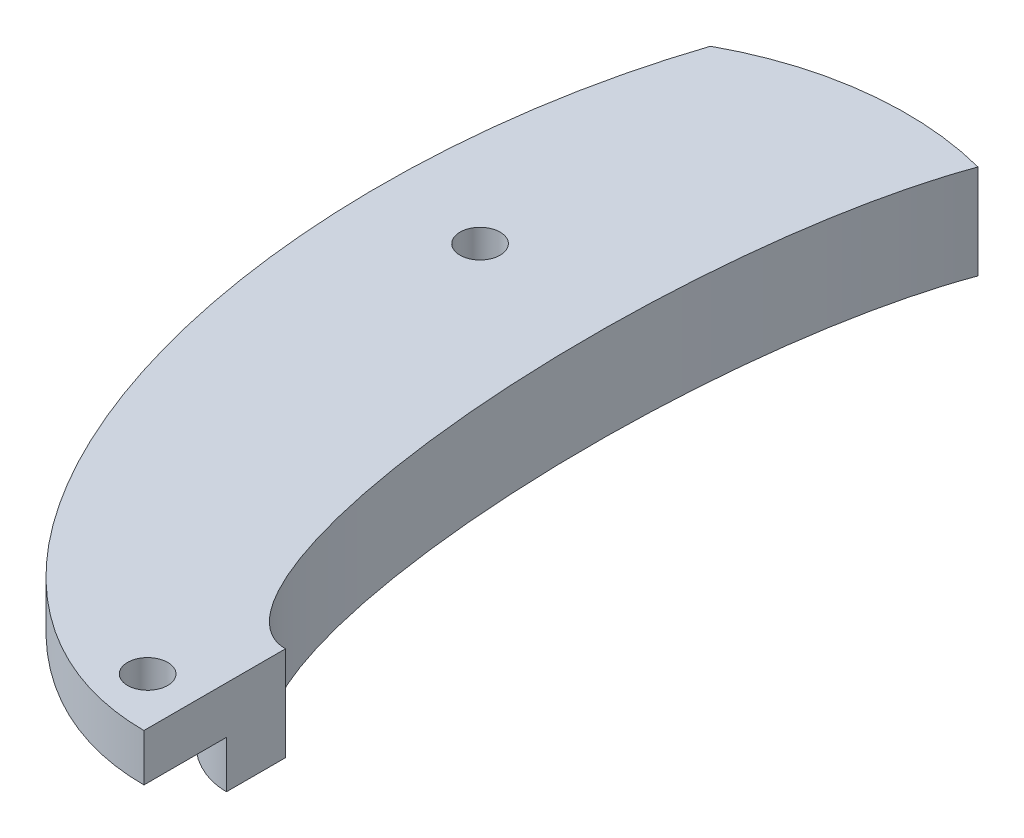
SolidWorks part; units mm, degrees
ref_plane "Спереди" through (0, 0, 0) normal (0, 0, 1) x (1, 0, 0)
ref_plane "Сверху" through (0, 0, 0) normal (0, 1, 0) x (1, 0, 0)
ref_plane "Справа" through (0, 0, 0) normal (1, 0, 0) x (0, 0, -1)
sketch "Эскиз1" plane through (0, 0, 0) normal (0, 1, 0) x (1, 0, 0)
  line L0 (0, -50) -> (0, -43)
  line L1 (0, 43) -> (0, 50) construction
  line L2 (0, 0) -> (-4.999, -57.1387) construction
  line L3 (0, 0) -> (-12.7544, -47.5999) construction
  line L5 (0, 0) -> (-46.6238, 0) construction
  circle A0 centre (-3.9973, -45.6893) radius 1.7
  arc A1 (-10.0001, 27.4752) -> (-26.23, 24.2663) centre (-13, 0) ccw
  circle A2 centre (-21.5, 0) radius 1.7
  ellipse E0 centre (0, 0) end of major axis (0, -43) minor radius 13 (-10.0001, 27.4752) -> (0, -43) ccw
  ellipse E1 centre (0, 0) end of major axis (0, -50) minor radius 30 (-26.23, 24.2663) -> (0, -50) ccw
  ellipse E2 centre (0, 0) end of major axis (0, -46.5) minor radius 21.5 (0, 46.5) -> (0, -46.5) ccw construction
  dimension "D1" = 43
  dimension "D10" = 3.4
  dimension "D11" = 3.4
  dimension "D2" = 13
  dimension "D3" = 30
  dimension "D4" = 50
  dimension "D5" = 21.5
  dimension "D6" = 46.5
  dimension "D7" = 5
  dimension "D8" = 15
extrude "Бобышка-Вытянуть1" add sketch "Эскиз1" along normal blind 4
sketch "Эскиз2" plane through (0, 4, 0) normal (0, 1, 0) x (1, 0, 0)
  line L0 (0, -43) -> (0, -38)
  arc A0 (-10.4108, 27.5169) -> (-6.0211, 26.7428) centre (-13, 0) cw
  ellipse E0 centre (0, -2) end of major axis (0, -38) minor radius 10 (-6.0211, 26.7428) -> (0, -38) ccw
  ellipse E1 centre (0, -2) end of major axis (0, -43) minor radius 15 (-10.4108, 27.5169) -> (0, -43) ccw
  ellipse E2 centre (0, 0) end of major axis (0, -43) minor radius 13 (-10.0001, 27.4752) -> (0, -43) ccw construction
  dimension "D3" = 5
  dimension "D1" = 10
  dimension "D2" = 5
  dimension "D4" = 36
extrude "Бобышка-Вытянуть2" add sketch "Эскиз2" against normal blind 8
